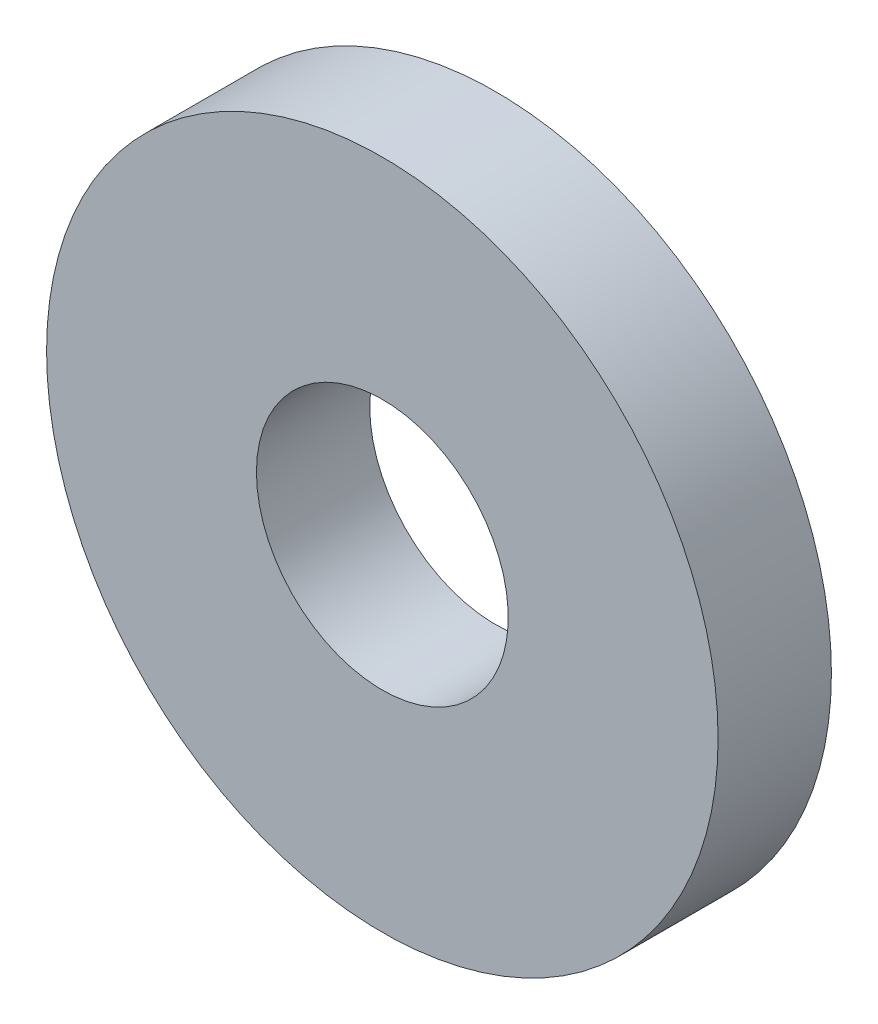
SolidWorks part; units mm, degrees
ref_plane "Přední rovina" through (0, 0, 0) normal (0, 0, 1) x (1, 0, 0)
ref_plane "Horní rovina" through (0, 0, 0) normal (0, 1, 0) x (1, 0, 0)
ref_plane "Pravá rovina" through (0, 0, 0) normal (1, 0, 0) x (0, 0, -1)
sketch "Skica1" plane through (0, 0, 0) normal (0, 0, 1) x (1, 0, 0)
  circle A0 centre (0, 0) radius 6
  circle A1 centre (0, 0) radius 16
  dimension "D1" = 32
  dimension "D2" = 12
extrude "Přidat vysunutím1" add sketch "Skica1" along normal blind 5.4
